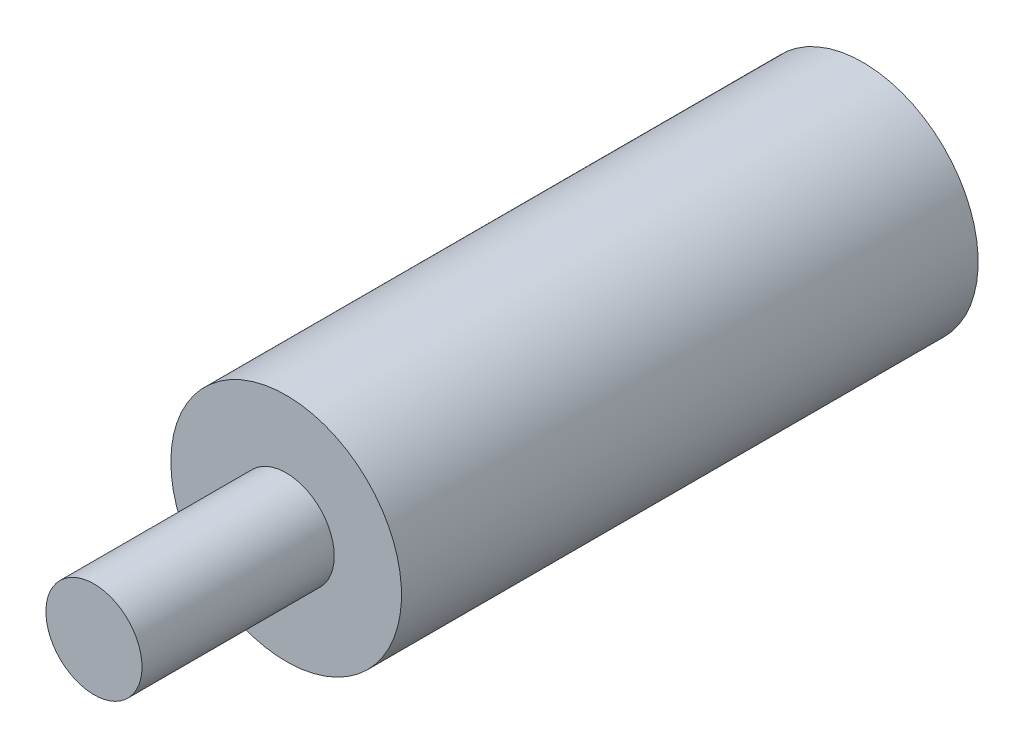
SolidWorks part; units mm, degrees
ref_plane "前视基准面" through (0, 0, 0) normal (0, 0, 1) x (1, 0, 0)
ref_plane "上视基准面" through (0, 0, 0) normal (0, 1, 0) x (1, 0, 0)
ref_plane "右视基准面" through (0, 0, 0) normal (1, 0, 0) x (0, 0, -1)
other "Configuration Table"
sketch "草图1" plane through (0, 0, 0) normal (0, 0, 1) x (1, 0, 0)
  circle A0 centre (0, 0) radius 2.5
  dimension "D1" = 5
extrude "凸台-拉伸1" add sketch "草图1" along normal mid plane 10
sketch "草图2" plane through (0, 0, -5) normal (0, 0, -1) x (-1, 0, 0)
  circle A0 centre (0, 0) radius 6
  dimension "D1" = 12
extrude "凸台-拉伸2" add sketch "草图2" along normal blind 30
